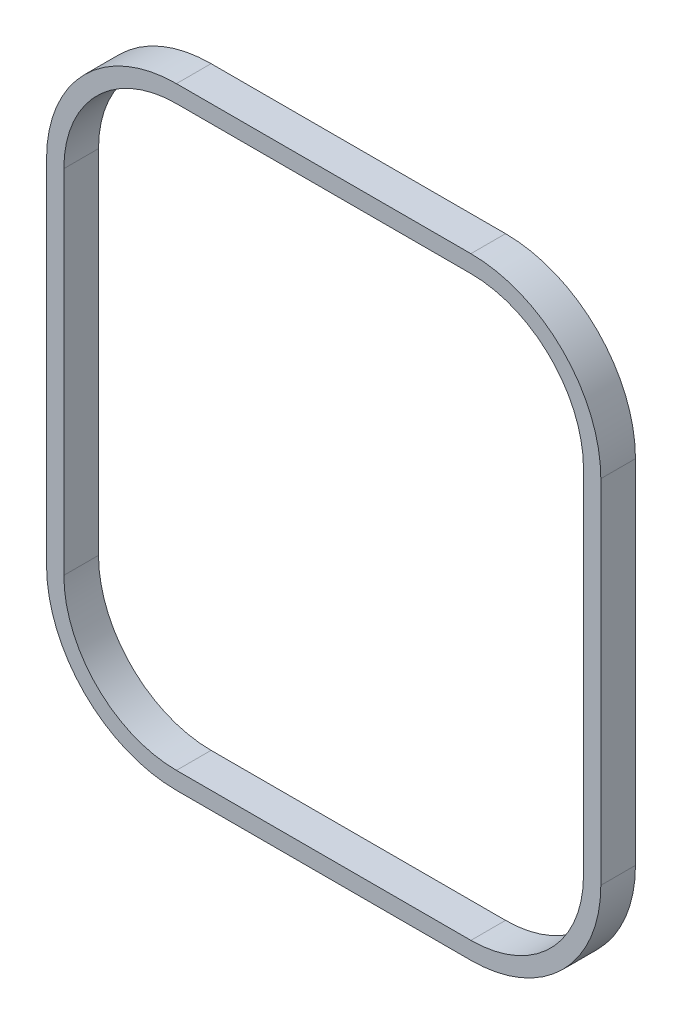
SolidWorks part; units mm, degrees
ref_plane "Спереди" through (0, 0, 0) normal (0, 0, 1) x (1, 0, 0)
ref_plane "Сверху" through (0, 0, 0) normal (0, 1, 0) x (1, 0, 0)
ref_plane "Справа" through (0, 0, 0) normal (1, 0, 0) x (0, 0, -1)
sketch "Эскиз1" plane through (0, 0, 0) normal (0, 0, 1) x (1, 0, 0)
  line L1 (-51, 100) -> (51, 100)
  line L2 (-90, 61) -> (-90, -61)
  line L3 (-51, -100) -> (51, -100)
  line L4 (90, 61) -> (90, -61)
  line L5 (-90, 100) -> (90, -100) construction
  line L6 (-90, -100) -> (90, 100) construction
  arc A0 (51, -100) -> (90, -61) centre (51, -61) ccw
  arc A1 (-90, -61) -> (-51, -100) centre (-51, -61) ccw
  arc A2 (51, 100) -> (90, 61) centre (51, 61) cw
  arc A3 (-51, 100) -> (-90, 61) centre (-51, 61) ccw
  point P0 (0, 0)
  dimension "D3" = 39
  dimension "D4" = 39
  dimension "D5" = 39
  dimension "D6" = 39
  dimension "D1" = 200
  dimension "D2" = 180
extrude "Вытянуть-Тонкостенный1" add sketch "Эскиз1" along normal blind 12 thin thin type one direction wall 6
